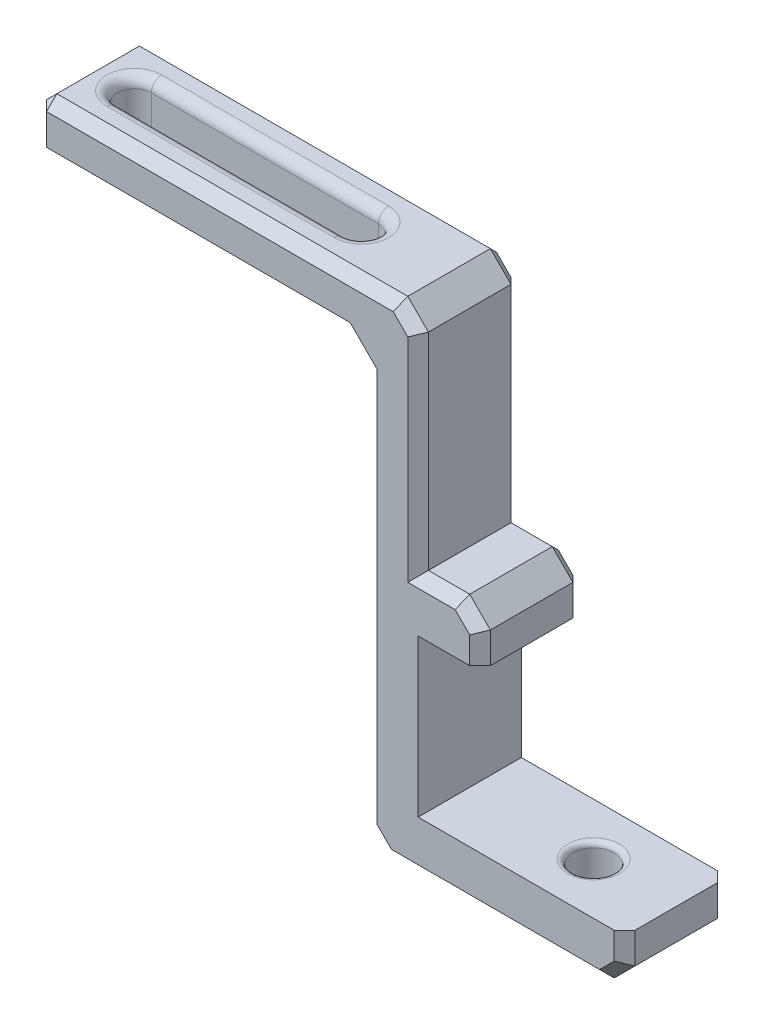
SolidWorks part; units mm, degrees
ref_plane "Plano frontal" through (0, 0, 0) normal (0, 0, 1) x (1, 0, 0)
ref_plane "Plano superior" through (0, 0, 0) normal (0, 1, 0) x (1, 0, 0)
ref_plane "Plano direito" through (0, 0, 0) normal (1, 0, 0) x (0, 0, -1)
sketch "Esboço1" plane through (0, 0, 0) normal (0, 0, 1) x (1, 0, 0)
  line L1 (1.8864, -7.75) -> (-4.1136, -7.75)
  line L2 (-4.1136, 19.25) -> (-4.1136, -2.75)
  line L3 (-4.1136, -22.95) -> (15.8864, -22.95)
  line L4 (15.8864, -22.95) -> (15.8864, -27.95)
  line L5 (15.8864, -27.95) -> (-9.1136, -27.95)
  line L6 (-9.1136, -27.95) -> (-9.1136, 14.25)
  line L7 (1.8864, -2.75) -> (1.8864, -7.75)
  line L8 (1.8864, -2.75) -> (-4.1136, -2.75)
  line L9 (-4.1136, -7.75) -> (-4.1136, -22.95)
  line L15 (-4.1136, 19.25) -> (-41.1136, 19.25)
  line L16 (-41.1136, 19.25) -> (-41.1136, 14.25)
  line L17 (-41.1136, 14.25) -> (-9.1136, 14.25)
  dimension "D1" = 5
  dimension "D2" = 20
  dimension "D3" = 15.2
  dimension "D4" = 6
  dimension "D5" = 5
  dimension "D6" = 5
  dimension "D7" = 17
  dimension "D8" = 5
  dimension "D9" = 32
extrude "Ressalto-extrusão1" add sketch "Esboço1" along normal blind 10
sketch "Esboço3" plane through (0, -27.95, 0) normal (0, -1, 0) x (1, 0, 0)
  line L0 (15.8864, 5) -> (7.8864, 5) construction
  line L1 (15.8864, 10) -> (15.8864, 0) construction
  circle A0 centre (7.8864, 5) radius 2
  dimension "D1" = 4
  dimension "D2" = 8
extrude "Corte-extrusão1" cut sketch "Esboço3" against normal blind 15
chamfer "Chanfro1" distance 1.6 angle 45 1 edges at (7.8864, -27.95, 3)
fillet "Filete1" radius 0.5 1 edges at (7.8864, -22.95, 3)
chamfer "Chanfro5" distance 2 angle 45 5 edges at (15.8864, -27.95, 5) (-9.1136, -27.95, 5) (1.8864, -2.75, 5) (-4.1136, 19.25, 5) (-9.1136, 14.25, 5)
chamfer "Chanfro8" distance 1 angle 45 30 edges at (-41.1136, 19.25, 5) (-41.1136, 16.75, 10) (-41.1136, 14.25, 5) (-41.1136, 16.75, 0) (1.8864, -6.25, 0) (0.8864, -3.75, 0) (-2.1136, -2.75, 0) (-4.1136, 7.25, 0) (-5.1136, 18.25, 0) (-23.6136, 19.25, 0) (15.8864, -24.45, 0) (14.8864, -26.95, 0) (3.3864, -27.95, 0) (-8.1136, -26.95, 0) (-9.1136, -6.85, 0) (-10.1136, 13.25, 0) (-26.1136, 14.25, 0) (15.8864, -24.45, 10) (14.8864, -26.95, 10) (3.3864, -27.95, 10) (-8.1136, -26.95, 10) (-9.1136, -6.85, 10) (-10.1136, 13.25, 10) (-26.1136, 14.25, 10) (1.8864, -6.25, 10) (0.8864, -3.75, 10) (-2.1136, -2.75, 10) (-4.1136, 7.25, 10) (-5.1136, 18.25, 10) (-23.6136, 19.25, 10)
sketch "Esboço4" plane through (0, 14.25, 0) normal (0, -1, 0) x (1, 0, 0)
  line L0 (-40.1136, 5) -> (-11.1136, 5) construction
  line L3 (-36.6136, 5) -> (-14.6136, 5) construction
  line L4 (-36.6136, 6.65) -> (-14.6136, 6.65)
  line L5 (-36.6136, 3.35) -> (-14.6136, 3.35)
  line L7 (-11.1136, 1) -> (-11.1136, 9) construction
  line L8 (-40.1136, 9) -> (-40.1136, 1) construction
  arc A0 (-36.6136, 6.65) -> (-36.6136, 3.35) centre (-36.6136, 5) ccw
  arc A1 (-14.6136, 3.35) -> (-14.6136, 6.65) centre (-14.6136, 5) ccw
  point P8 (-25.6136, 5)
  point P17 (-25.6136, 5)
  dimension "D1" = 22
  dimension "D2" = 3.3
extrude "Corte-extrusão3" cut sketch "Esboço4" against normal blind 10
fillet "Filete3" radius 1 8 edges at (-38.2636, 19.25, 5) (-25.6136, 19.25, 6.65) (-12.9636, 19.25, 5) (-38.2636, 14.25, 5) (-25.6136, 14.25, 6.65) (-12.9636, 14.25, 5) (-25.6136, 19.25, 3.35) (-25.6136, 14.25, 3.35)
